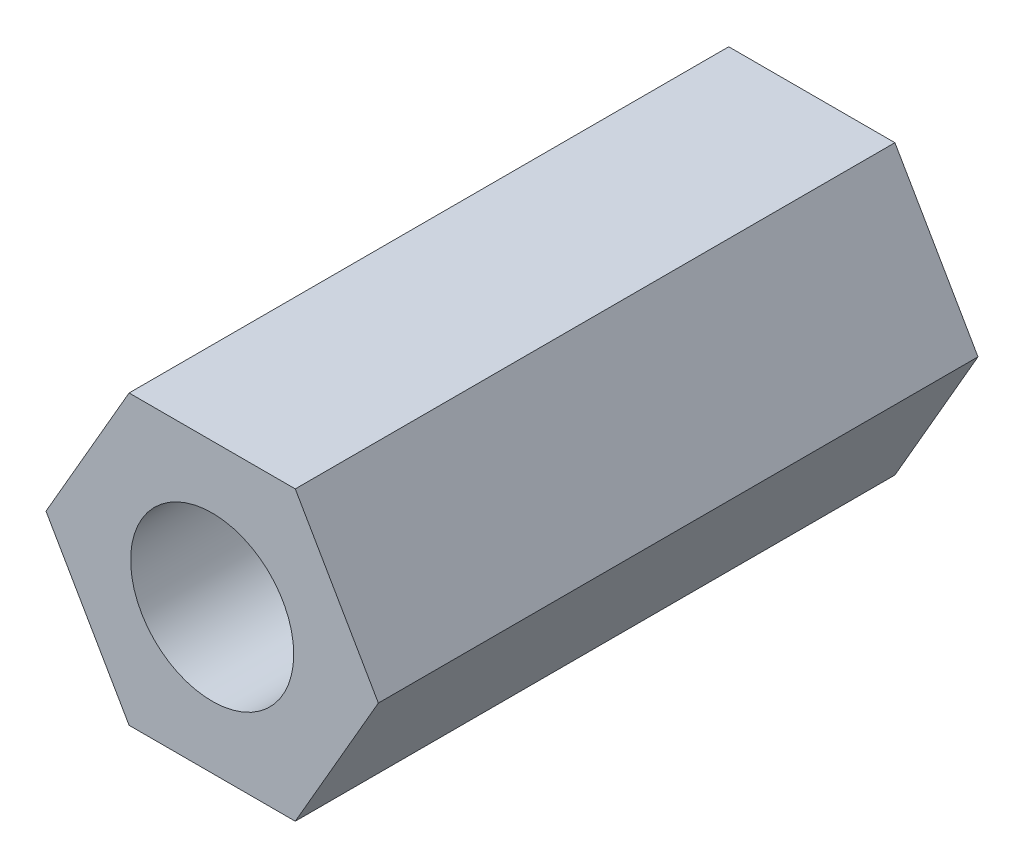
SolidWorks part; units mm, degrees
material "Оцинкованная сталь"
ref_plane "Front" through (0, 0, 0) normal (0, 0, 1) x (1, 0, 0)
ref_plane "Top" through (0, 0, 0) normal (0, 1, 0) x (1, 0, 0)
ref_plane "Right" through (0, 0, 0) normal (1, 0, 0) x (0, 0, -1)
sketch "Эскиз1" plane through (0, 0, 0) normal (0, 0, 1) x (1, 0, 0)
  line L1 (6.9282, 0) -> (3.4641, 6)
  line L2 (3.4641, 6) -> (-3.4641, 6)
  line L3 (-3.4641, 6) -> (-6.9282, 0)
  line L4 (-6.9282, 0) -> (-3.4641, -6)
  line L5 (-3.4641, -6) -> (3.4641, -6)
  line L6 (3.4641, -6) -> (6.9282, 0)
  circle A0 centre (0, 0) radius 6 construction
  dimension "D1" = 12
extrude "Бобышка-Вытянуть1" add sketch "Эскиз1" against normal blind 25
hole_wizard "M8" positions "Эскиз2" profile "Эскиз3" tap size "M8" standard "DIN" end condition through all
sketch "Эскиз2" plane through (0, 0, 0) normal (0, 0, 1) x (1, 0, 0)
  point P0 (0, 0)
sketch "Эскиз3" plane through (0, 0, 0) normal (1, 0, 0) x (0, -1, 0)
  line L0 (0, 0) -> (0, 25)
  line L1 (0, 25) -> (3.4, 25)
  line L2 (3.4, 25) -> (3.4, 0)
  line L5 (3.4, 0) -> (0, 0)
  line L11 (0, -6.35) -> (0, 107.95) construction
  dimension "Диаметр проходного сверла" = 6.8
  dimension "Глубина проходного сверла" = 25
cosmetic thread "Отверстие резьбы1" parameters "D2"=8
